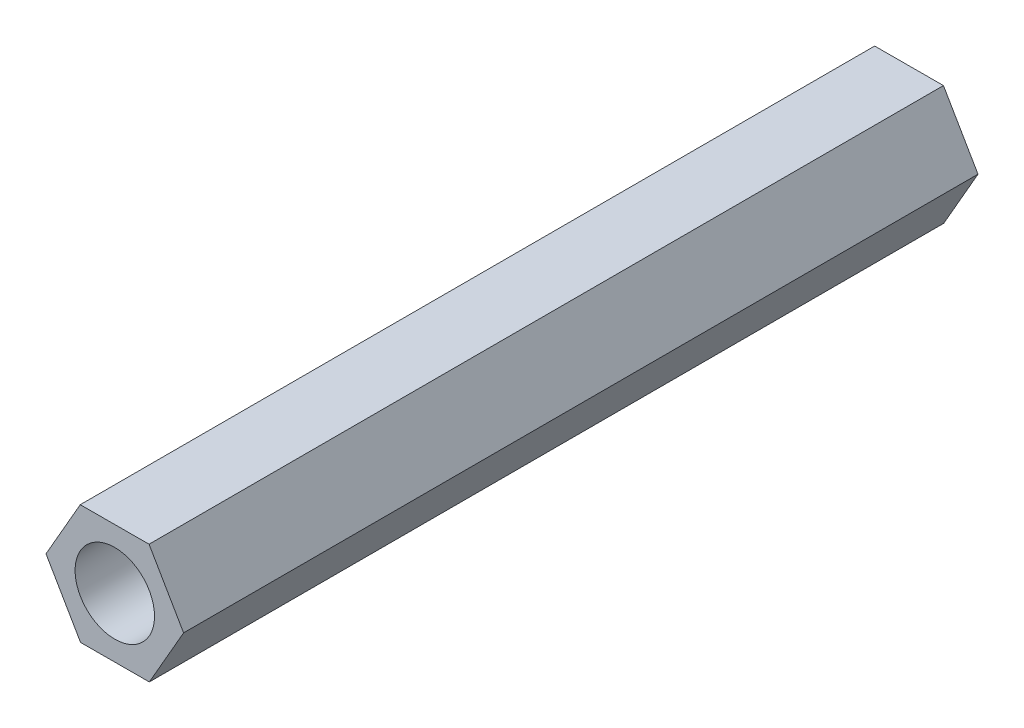
SolidWorks part; units mm, degrees
ref_plane "前视基准面" through (0, 0, 0) normal (0, 0, 1) x (1, 0, 0)
ref_plane "上视基准面" through (0, 0, 0) normal (0, 1, 0) x (1, 0, 0)
ref_plane "右视基准面" through (0, 0, 0) normal (1, 0, 0) x (0, 0, -1)
sketch "草图1" plane through (0, 0, 0) normal (0, 0, 1) x (1, 0, 0)
  line L1 (1.7391, -2.9959) -> (3.4641, 0.0082)
  line L2 (3.4641, 0.0082) -> (1.7249, 3.0041)
  line L3 (1.7249, 3.0041) -> (-1.7391, 2.9959)
  line L4 (-1.7391, 2.9959) -> (-3.4641, -0.0082)
  line L5 (-3.4641, -0.0082) -> (-1.7249, -3.0041)
  line L6 (-1.7249, -3.0041) -> (1.7391, -2.9959)
  circle A1 centre (0, 0) radius 3 construction
  circle A2 centre (0, 0) radius 2
extrude "凸台-拉伸1" add sketch "草图1" along normal blind 40
